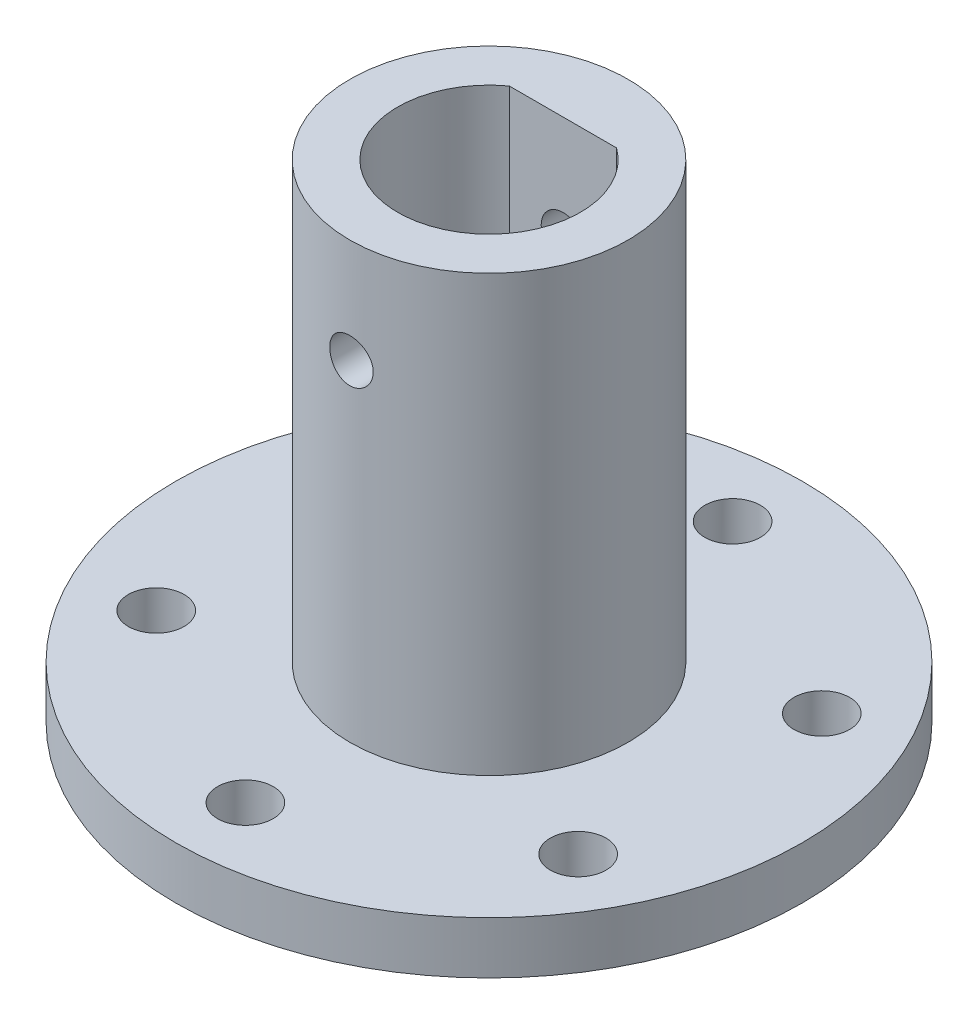
SolidWorks part; units mm, degrees
material "合金钢"
ref_plane "前视基准面" through (0, 0, 0) normal (0, 0, 1) x (1, 0, 0)
ref_plane "上视基准面" through (0, 0, 0) normal (0, 1, 0) x (1, 0, 0)
ref_plane "右视基准面" through (0, 0, 0) normal (1, 0, 0) x (0, 0, -1)
sketch "草图1" plane through (0, 0, 0) normal (0, 0, 1) x (1, 0, 0)
  line L0 (0, 12.8439) -> (0, -12.3272) construction
  line L1 (-5.25, 0) -> (-18, 0)
  line L2 (-18, 0) -> (-18, 3)
  line L3 (-18, 3) -> (-8, 3)
  line L4 (-8, 3) -> (-8, 28)
  line L5 (-8, 28) -> (-5.25, 28)
  line L6 (-5.25, 28) -> (-5.25, 0)
  dimension "D1" = 18
  dimension "D2" = 10.5
  dimension "D3" = 16
  dimension "D4" = 3
  dimension "D5" = 28
revolve "旋转1" add sketch "草图1" angle 360 about L0
sketch "草图2" plane through (0, 3, 0) normal (0, 1, 0) x (1, 0, 0)
  circle A0 centre (0, 0) radius 14 construction
  circle A1 centre (0, 14) radius 1.6
  circle A2 centre (12.1244, 7) radius 1.6
  circle A3 centre (12.1244, -7) radius 1.6
  circle A4 centre (0, -14) radius 1.6
  circle A5 centre (-12.1244, -7) radius 1.6
  circle A6 centre (-12.1244, 7) radius 1.6
  point P17 (0, 0)
  dimension "D1" = 28
  dimension "D2" = 3.2
  dimension "D3" = 6
extrude "切除-拉伸1" cut sketch "草图2" against normal blind 10
sketch "草图3" plane through (0, 28, 0) normal (0, 1, 0) x (1, 0, 0)
  line L0 (-3.0822, 4.25) -> (3.0822, 4.25)
  circle A0 centre (0, 0) radius 5.25 construction
  arc A1 (3.0822, 4.25) -> (-3.0822, 4.25) centre (0, 0) ccw
  point P3 (0, 5.25)
  dimension "D1" = 1
extrude "凸台-拉伸1" add sketch "草图3" against normal up to surface (28 mm away) up to face at (12.1244, 0, -8.6)
sketch "草图4" plane through (0, 0, -4.25) normal (0, 0, 1) x (1, 0, 0)
  line L0 (5.25, 28) -> (-5.25, 28) construction
  line L1 (-8, 28) -> (-8, 3) construction
  circle A0 centre (0, 22) radius 1.5
  dimension "D1" = 3
  dimension "D2" = 6
  dimension "D3" = 8
ref_plane "基准面1" through (0, 0, -10) normal (0, 0, 1) x (1, 0, 0)
sketch "草图7" plane through (0, 0, -10) normal (0, 0, 1) x (1, 0, 0)
  point P0 (0, 22)
hole_wizard "M3 螺纹孔2" positions "草图8" profile "草图9" tap size "M3" standard "GB" end condition through all
sketch "草图8" plane through (0, 0, -10) normal (0, 0, 1) x (1, 0, 0)
  point P0 (0, 22)
sketch "草图9" plane through (0, 22, -10) normal (1, 0, 0) x (0, 1, 0)
  line L0 (0, 0) -> (0, 28)
  line L1 (0, 28) -> (1.25, 28)
  line L2 (1.25, 28) -> (1.25, 0)
  line L5 (1.25, 0) -> (0, 0)
  line L11 (0, -6.35) -> (0, 107.95) construction
  dimension "通孔螺纹孔钻头直径" = 2.5
  dimension "通孔螺纹孔钻头深度" = 28
cosmetic thread "孔螺蚊线2" parameters "D2"=3
